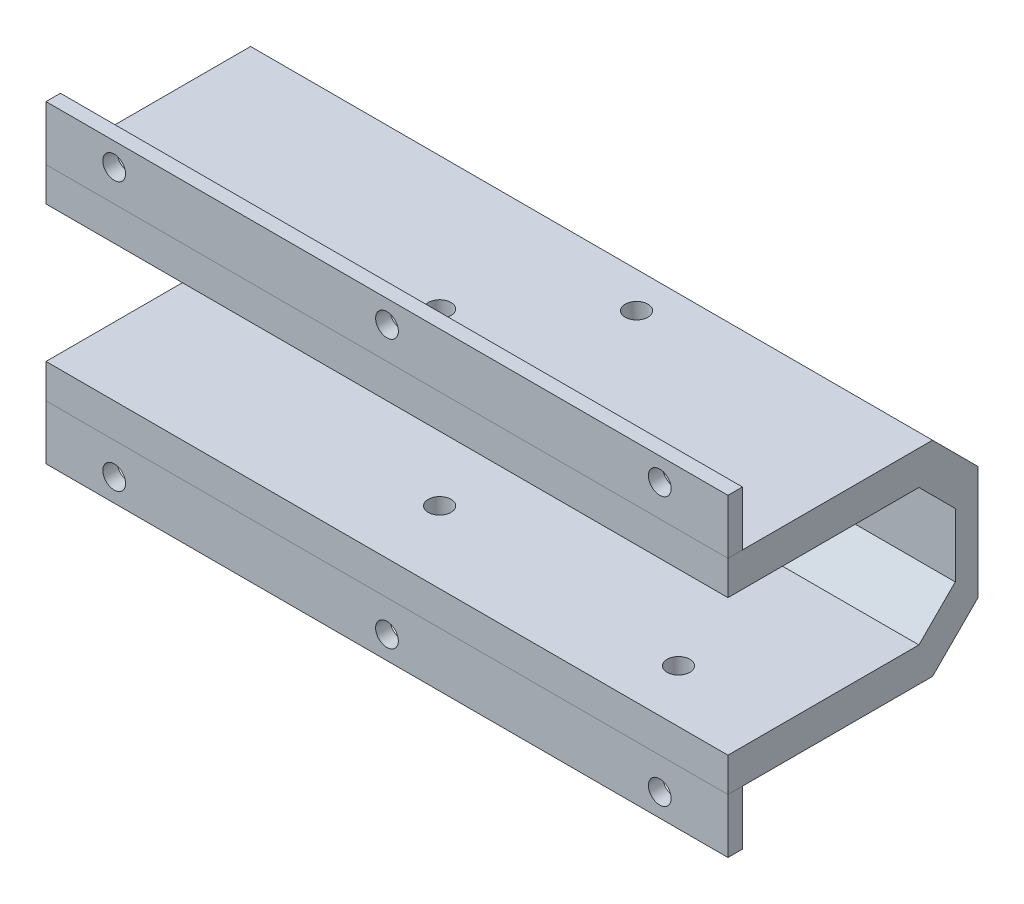
SolidWorks part; units mm, degrees
ref_plane "Front Plane" through (0, 0, 0) normal (0, 0, 1) x (1, 0, 0)
ref_plane "Top Plane" through (0, 0, 0) normal (0, 1, 0) x (1, 0, 0)
ref_plane "Right Plane" through (0, 0, 0) normal (1, 0, 0) x (0, 0, -1)
sketch "Sketch1" plane through (0, 0, 0) normal (0, 0, 1) x (1, 0, 0)
  line L1 (0, 0) -> (150, 0)
  line L2 (0, 0) -> (0, 45)
  line L3 (0, 45) -> (150, 45)
  line L4 (150, 0) -> (150, 45)
  dimension "D1" = 150
  dimension "D2" = 45
extrude "Boss-Extrude1" add sketch "Sketch1" along normal blind 55
sketch "Sketch2" plane through (150, 0, 0) normal (1, 0, 0) x (0, 0, -1)
  line L0 (-55, 37.5) -> (-13, 37.5)
  line L1 (-55, 0) -> (-55, 45) construction
  line L2 (-55, 22.5) -> (0, 22.5) construction
  line L3 (0, 0) -> (0, 45) construction
  line L4 (-5, 15.5) -> (-5, 29.5)
  line L5 (-13, 37.5) -> (-5, 29.5)
  line L6 (-13, 7.5) -> (-5, 15.5)
  line L7 (-55, 7.5) -> (-13, 7.5)
  point P10 (-5, 22.5)
  dimension "D1" = 42
  dimension "D2" = 135
  dimension "D3" = 50
  dimension "D4" = 15
extrude "Cut-Extrude1" cut sketch "Sketch2" against normal through all and the other way through all
chamfer "Chamfer1" distance 10 angle 45 2 edges at (75, 45, 0) (75, 0, 0)
sketch "Sketch3" plane through (0, 45, 0) normal (0, 1, 0) x (1, 0, 0)
  circle A0 centre (92.7807, -17.8822) radius 2.5
  circle A1 centre (127.534, -43.4218) radius 2.5
  circle A2 centre (70.7973, -39.2191) radius 2.5
  dimension "D1" = 5
extrude "Cut-Extrude2" cut sketch "Sketch3" against normal through all
sketch "Sketch4" plane through (0, 0, 55) normal (0, 0, 1) x (1, 0, 0)
  line L0 (150, 37.5) -> (150, 45) construction
  line L1 (0, 45) -> (150, 45)
  line L2 (0, 45) -> (0, 57)
  line L3 (0, 57) -> (150, 57)
  line L4 (150, 45) -> (150, 57)
  line L5 (0, 22.5) -> (150, 22.5) construction
  line L6 (0, 29.5) -> (0, 15.5) construction
  line L7 (150, 15.5) -> (150, 29.5) construction
  line L9 (150, 0) -> (150, -12)
  line L10 (0, -12) -> (150, -12)
  line L11 (0, 0) -> (0, -12)
  line L12 (0, 0) -> (150, 0)
  circle A0 centre (15, 52) radius 2.5
  circle A1 centre (75, 52) radius 2.5
  circle A2 centre (135, 52) radius 2.5
  circle A3 centre (135, -7) radius 2.5
  circle A4 centre (75, -7) radius 2.5
  circle A5 centre (15, -7) radius 2.5
  dimension "D2" = 15
  dimension "D3" = 15
  dimension "D4" = 60
  dimension "D5" = 60
  dimension "D6" = 5
  dimension "D7" = 5
  dimension "D1" = 12
extrude "Boss-Extrude2" add sketch "Sketch4" against normal blind 3.175 separate body
